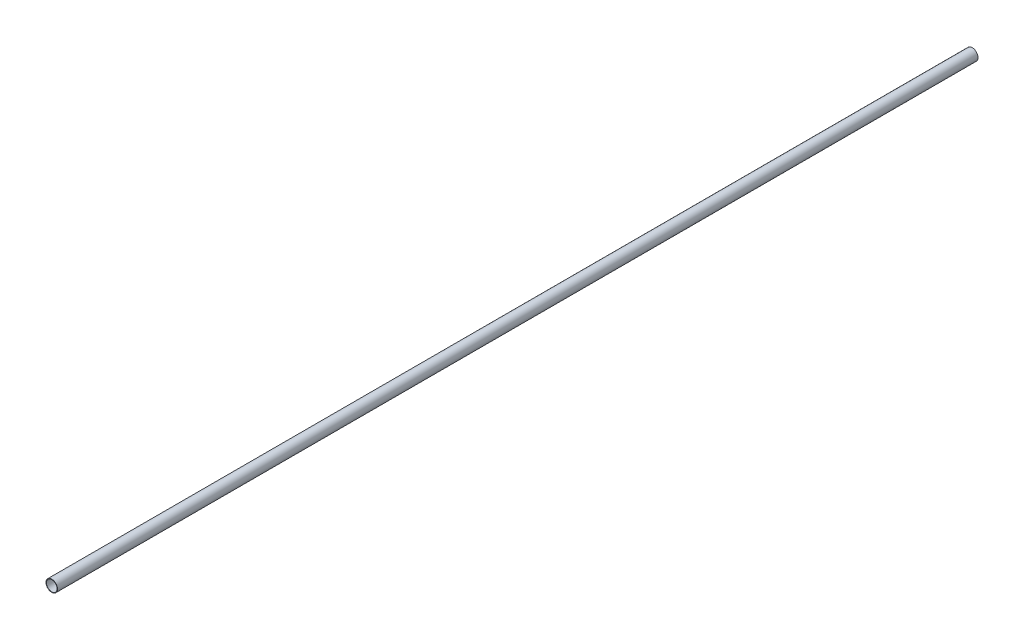
SolidWorks part; units mm, degrees
material "windcatcher"
ref_plane "Front Plane" through (0, 0, 0) normal (0, 0, 1) x (1, 0, 0)
ref_plane "Top Plane" through (0, 0, 0) normal (0, 1, 0) x (1, 0, 0)
ref_plane "Right Plane" through (0, 0, 0) normal (1, 0, 0) x (0, 0, -1)
sketch "Sketch1" plane through (0, 0, 0) normal (0, 0, 1) x (1, 0, 0)
  circle A0 centre (0, 0) radius 12.5
  circle A1 centre (0, 0) radius 11.5
  dimension "D1" = 25
  dimension "D2" = 23
extrude "Boss-Extrude1" add sketch "Sketch1" against normal blind 2000
